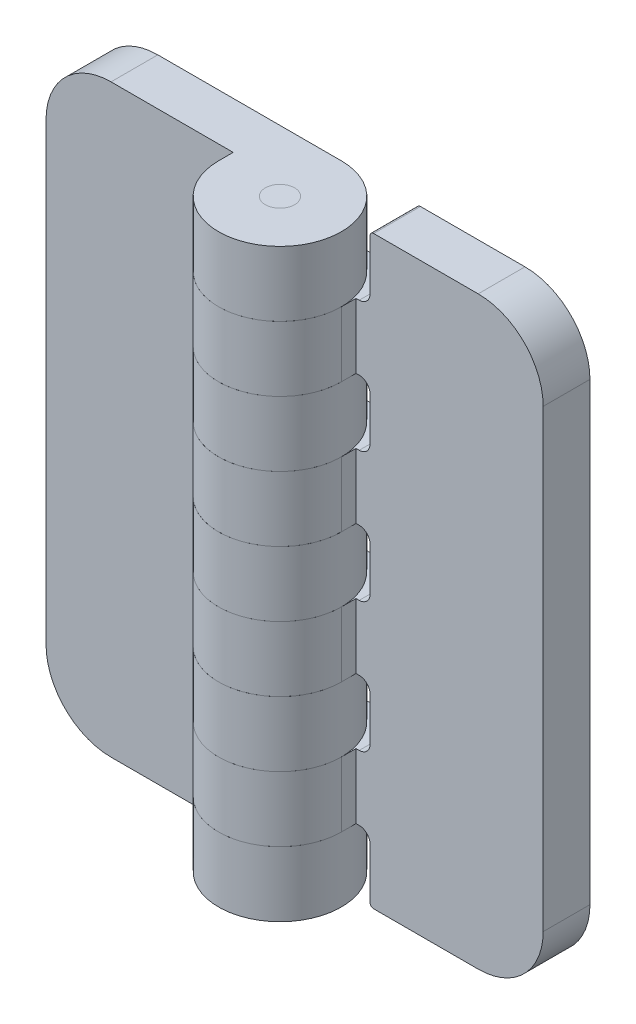
SolidWorks part; units mm, degrees
ref_plane "Front Plane" through (0, 0, 0) normal (0, 0, 1) x (1, 0, 0)
ref_plane "Top Plane" through (0, 0, 0) normal (0, 1, 0) x (1, 0, 0)
ref_plane "Right Plane" through (0, 0, 0) normal (1, 0, 0) x (0, 0, -1)
sketch "Sketch1" plane through (0, 0, 0) normal (0, 0, 1) x (1, 0, 0)
  line L0 (0, -31.75) -> (0, 31.75) construction
  line L1 (1.5875, 31.75) -> (1.5875, -31.75)
  line L2 (-26.9875, 31.75) -> (26.9875, 31.75)
  line L3 (-26.9875, 31.75) -> (-26.9875, -31.75)
  line L4 (-26.9875, -31.75) -> (26.9875, -31.75)
  line L5 (26.9875, 31.75) -> (26.9875, -31.75)
  line L6 (-1.5875, 31.75) -> (-1.5875, -31.75)
  dimension "Frame Leaf Width" = 26.9875
  dimension "Frame Leaf Height" = 63.5
  dimension "Door Leaf Height" = 63.5
  dimension "Door Leaf Width" = 26.9875
  dimension "Overall Width" = 53.975
  dimension "Pin Diameter" = 3.175
sketch "Sketch2" plane through (0, 0, 0) normal (0, 1, 0) x (1, 0, 0)
  line L1 (-26.9875, 6.6675) -> (26.9875, 6.6675)
  line L2 (-26.9875, 6.6675) -> (-26.9875, 1.5875)
  line L3 (-26.9875, 1.5875) -> (26.9875, 1.5875)
  line L4 (26.9875, 6.6675) -> (26.9875, 1.5875)
  circle A0 centre (0, 0) radius 1.5875
  circle A1 centre (0, 0) radius 6.6675
  dimension "D1" = 3.175
  dimension "Leaf Thickness" = 5.08
sketch "Sketch3" plane through (0, 0, 0) normal (0, 1, 0) x (1, 0, 0)
  line L0 (26.9875, 6.6675) -> (26.9875, 1.5875) construction
  line L2 (-26.9875, 6.6675) -> (26.9875, 6.6675) construction
  line L3 (-26.9875, 1.5875) -> (26.9875, 1.5875) construction
  line L4 (26.9875, 6.6675) -> (26.9875, 1.5875)
  line L6 (0, 6.6675) -> (26.9875, 6.6675)
  line L7 (6.6675, 1.5875) -> (26.9875, 1.5875)
  line L8 (6.6675, 0) -> (6.6675, 1.5875)
  circle A0 centre (0, 0) radius 1.5875 construction
  circle A1 centre (0, 0) radius 6.6675 construction
  circle A2 centre (0, 0) radius 1.5875
  arc A3 (0, 6.6675) -> (6.6675, 0) centre (0, 0) ccw
extrude "Boss-Extrude1" add sketch "Sketch3" against normal up to vertex (31.75 mm away) from vertex at 31.75 starting at point (26.9875, 31.75, 0)
fillet "Fillet1" radius 7.0556 2 edges at (26.9875, 31.75, -4.1275) (26.9875, -31.75, -4.1275)
mirror "Mirror1" about plane through (0, 0, 0) normal (1, 0, 0) of bodies 104
sketch "Sketch5" plane through (0, 0, 0) normal (0, 0, 1) x (1, 0, 0)
  line L0 (-26.9875, 31.75) -> (26.9875, 31.75) construction
  line L1 (-8.1915, 31.75) -> (8.1915, 31.75)
  line L2 (-8.1915, 31.75) -> (-8.1915, 24.6944)
  line L3 (-8.1915, 24.6944) -> (8.1915, 24.6944)
  line L4 (8.1915, 31.75) -> (8.1915, 24.6944)
  line L5 (6.6675, -31.75) -> (6.6675, 31.75) construction
  dimension "D1" = 7.0556
  dimension "D2" = 1.524
extrude "Cut-Extrude1" cut sketch "Sketch5" against normal through all both and the other way through all
pattern_linear "LPattern1" count 5 spacing 14.1111 along (0, -1, 0) of "Cut-Extrude1"
fillet "Fillet2" radius 1.1759 8 edges at (8.1915, 24.6944, -4.1275) (8.1915, -24.6944, -4.1275) (8.1915, -17.6389, -4.1275) (8.1915, -10.5833, -4.1275) (8.1915, 3.5278, -4.1275) (8.1915, -3.5278, -4.1275) (8.1915, 10.5833, -4.1275) (8.1915, 17.6389, -4.1275)
sketch "Sketch6" plane through (0, 0, 0) normal (0, 0, 1) x (1, 0, 0)
  line L0 (8.1915, 31.75) -> (8.1915, 24.6944) construction
  line L1 (-8.1915, 24.6944) -> (8.1915, 24.6944)
  line L2 (-8.1915, 24.6944) -> (-8.1915, 17.6389)
  line L3 (-8.1915, 17.6389) -> (8.1915, 17.6389)
  line L4 (8.1915, 24.6944) -> (8.1915, 17.6389)
extrude "Cut-Extrude2" cut sketch "Sketch6" against normal through all both and the other way through all
pattern_linear "LPattern2" count 4 spacing 14.1111 along (0, -1, 0) of "Cut-Extrude2"
fillet "Fillet3" radius 1.1759 8 edges at (-8.1915, -24.6944, -4.1275) (-8.1915, -17.6389, -4.1275) (-8.1915, -10.5833, -4.1275) (-8.1915, -3.5278, -4.1275) (-8.1915, 3.5278, -4.1275) (-8.1915, 10.5833, -4.1275) (-8.1915, 17.6389, -4.1275) (-8.1915, 24.6944, -4.1275)
fillet "Fillet4" radius 0.392 2 edges at (8.1915, -31.75, -4.1275) (8.1915, 31.75, -4.1275)
sketch "Sketch7" plane through (0, 0, 0) normal (0, 1, 0) x (1, 0, 0)
  circle A0 centre (0, 0) radius 1.5875 construction
  circle A1 centre (0, 0) radius 1.5875
extrude "Boss-Extrude3" add sketch "Sketch7" against normal up to vertex (31.75 mm away) from vertex at 31.75 separate body starting at point (-26.9875, 31.75, 0)
equation "\"D1@Sketch2\"=\"Pin Diameter@Sketch1\""
equation "\"D1@Fillet1\"=\"Frame Leaf Height@Sketch1\"/9"
equation "\"D1@Sketch5\"=\"Frame Leaf Height@Sketch1\"/9"
equation "\"D3@LPattern1\"=(\"Frame Leaf Height@Sketch1\"/9)*2"
equation "\"D3@LPattern2\"=(\"Frame Leaf Height@Sketch1\"/9)*2"
equation "\"D1@Fillet2\"=(\"Frame Leaf Height@Sketch1\"/9)/6"
equation "\"D1@Fillet3\"=(\"Frame Leaf Height@Sketch1\"/9)/6"
equation "\"D1@Fillet4\"=(\"Frame Leaf Height@Sketch1\"/9)/18"
